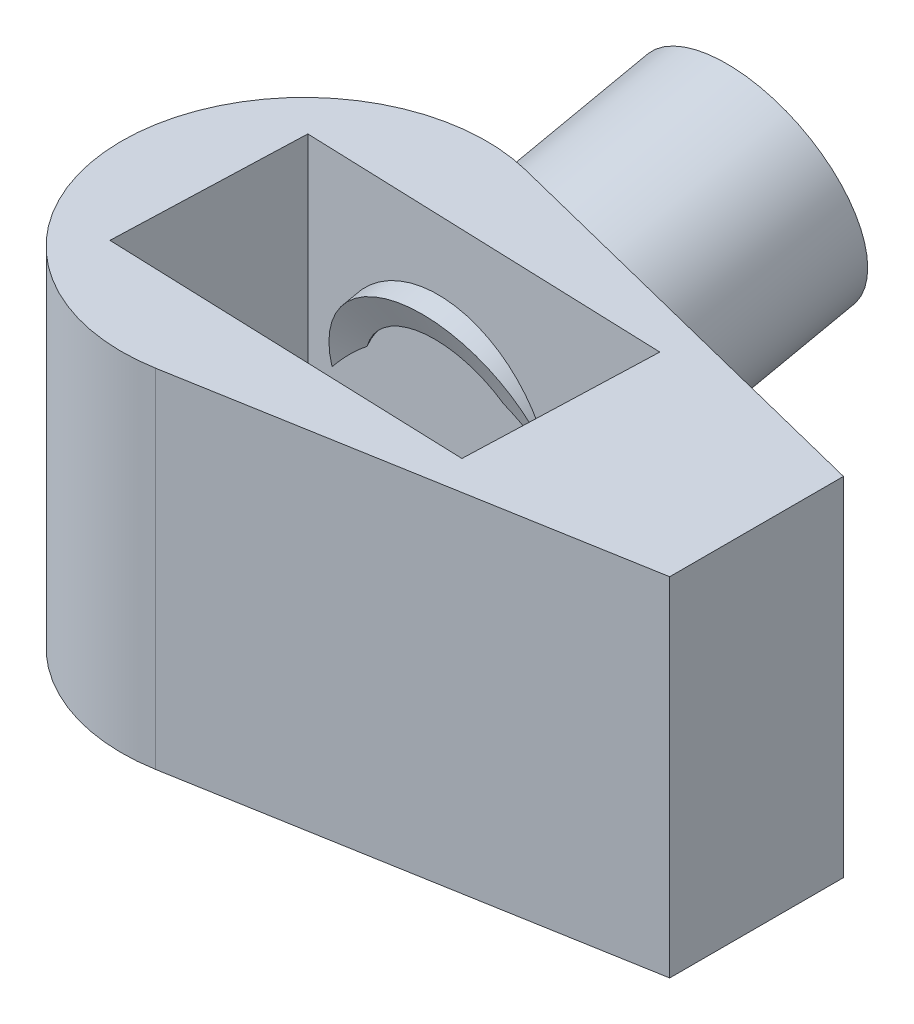
SolidWorks part; units mm, degrees
material "3.0205 (EN-AW 1200)"
ref_plane "Alzado" through (0, 0, 0) normal (0, 0, 1) x (1, 0, 0)
ref_plane "Planta" through (0, 0, 0) normal (0, 1, 0) x (1, 0, 0)
ref_plane "Vista lateral" through (0, 0, 0) normal (1, 0, 0) x (0, 0, -1)
sketch "Croquis1" plane through (0, 0, 0) normal (0, 1, 0) x (1, 0, 0)
  circle A0 centre (0, 0) radius 21
  dimension "D1" = 42
extrude "Saliente-Extruir1" add sketch "Croquis1" along normal blind 40
sketch "Croquis2" plane through (0, 0, 0) normal (0, 1, 0) x (1, 0, 0)
  line L0 (53.9751, 8.111) -> (53.9751, -11.889)
  line L1 (53.9751, -11.889) -> (3.6138, -20.6867)
  line L2 (53.9751, 8.111) -> (5.1095, 20.3689)
  circle A0 centre (0, 0) radius 21 construction
  arc A1 (3.6138, -20.6867) -> (5.1095, 20.3689) centre (0, 0) ccw
  dimension "D1" = 20
extrude "Saliente-Extruir2" add sketch "Croquis2" along normal blind 40
sketch "Croquis3" plane through (5.1095, 0, -20.3689) normal (0.2433, 0, -0.9699) x (-0.9699, 0, -0.2433)
  line L0 (0, 40) -> (0, 0) construction
  circle A0 centre (0, 20) radius 10
  circle A1 centre (0, 20) radius 13.5
  dimension "D1" = 20
  dimension "D2" = 27
extrude "Saliente-Extruir3" add sketch "Croquis3" against normal up to surface (2.5338 mm away)
ref_plane "Plano1" through (5.1, 0, 0) normal (1, 0, 0) x (0, 0, -1)
sketch "Croquis4" plane through (5.1, 0, 0) normal (1, 0, 0) x (0, 0, -1)
  line L0 (13.9987, 5.7083) -> (49.0384, 13.1635)
  line L1 (20.8384, 7.1635) -> (49.0384, 7.1635)
  line L2 (49.0384, 7.1635) -> (49.0384, 13.1635)
  line L3 (20.8384, 10.6635) -> (49.0384, 16.6635)
  line L4 (49.0384, 16.6635) -> (49.0384, 13.1635)
  line L5 (13.9987, 9.2083) -> (13.9987, 5.7083)
  line L6 (20.8384, 10.6635) -> (13.9987, 9.2083)
  line L7 (20.8384, 20.6635) -> (44.5117, 25.7004)
  line L10 (-1.889, 40) -> (-1.889, 0)
  line L11 (-11.889, 40) -> (8.111, 40) construction
  line L12 (-11.889, 0) -> (8.111, 0) construction
sketch "Croquis7" plane through (0, 0, 0) normal (0, -1, 0) x (1, 0, 0)
  circle A0 centre (0, 0) radius 6
  circle A1 centre (0, 0) radius 8.2273
  dimension "D1" = 16.4545
  dimension "D2" = 12
extrude "Cortar-Extruir6" cut sketch "Croquis7" against normal blind 6
sketch "Croquis8" plane through (0, 0, 0) normal (0, -1, 0) x (1, 0, 0)
  circle A0 centre (0, 0) radius 6
extrude "Cortar-Extruir7" cut sketch "Croquis8" against normal through all
sketch "Croquis10" plane through (0, 40, 0) normal (0, 1, 0) x (1, 0, 0)
  line L0 (-11.3782, 0.4245) -> (30.6218, -1.0623)
  line L1 (-10.9888, 11.4245) -> (31.0112, 9.9377)
  line L2 (-10.9888, 11.4245) -> (-11.7676, -10.5755)
  line L3 (31.0112, 9.9377) -> (30.2324, -12.0623)
  line L4 (-11.7676, -10.5755) -> (30.2324, -12.0623)
  line L5 (37.4945, -5.951) -> (37.4945, -5.9648)
  line L7 (53.9751, -1.889) -> (-20.9861, 0.7646)
  line L8 (53.9751, -11.889) -> (53.9751, 8.111) construction
  arc A0 (5.1095, 20.3689) -> (3.6138, -20.6867) centre (0, 0) ccw construction
  point P7 (16.4945, -0.5622)
  circle M7 centre (0, 0) radius 6
  dimension "D1" = 11
  dimension "D2" = 42
extrude "Cortar-Extruir8" cut sketch "Croquis10" against normal blind 25 contours L2 L4 L3 L0 M7 | L3 L1 L2 L0 M7
sketch "Croquis12" plane through (0, 15, 0) normal (0, 1, 0) x (1, 0, 0)
  circle A0 centre (0, 0) radius 9.55
  dimension "D1" = 19.1
extrude "Cortar-Extruir9" cut sketch "Croquis12" against normal blind 5.5
sketch "Croquis15" plane through (53.9751, 0, 0) normal (1, 0, 0) x (0, 0, -1)
sketch "Croquis17" plane through (0, 40, 0) normal (0, 1, 0) x (1, 0, 0)
  line L0 (5.1095, 20.3689) -> (5.1095, 31.6806)
  line L1 (5.1095, 31.6806) -> (-13.6883, 31.6806)
  line L2 (-13.6883, 31.6806) -> (-13.6883, 15.9257)
  arc A0 (5.1095, 20.3689) -> (-13.6883, 15.9257) centre (0, 0) ccw
extrude "Cortar-Extruir10" cut sketch "Croquis17" against normal through all contours A0 L2 L1 L0
revolve "Revolución1" add sketch "Croquis4" angle 360 about L7
